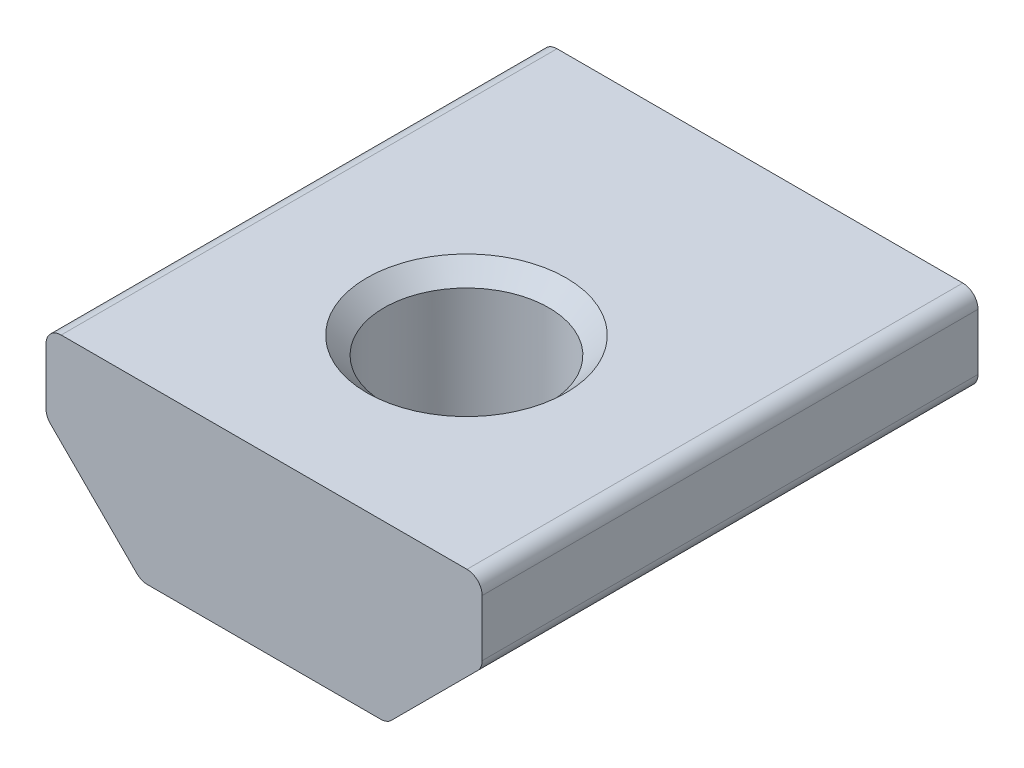
SolidWorks part; units mm, degrees
ref_plane "Front Plane" through (0, 0, 0) normal (0, 0, 1) x (1, 0, 0)
ref_plane "Top Plane" through (0, 0, 0) normal (0, 1, 0) x (1, 0, 0)
ref_plane "Right Plane" through (0, 0, 0) normal (1, 0, 0) x (0, 0, -1)
ref_plane "Plane1" through (0, 0, 5.08) normal (0, 0, 1) x (1, 0, 0)
sketch "Sketch1" plane through (0, 0, 5.08) normal (0, 0, 1) x (1, 0, 0)
  line L0 (5.4737, 4.3434) -> (-5.4737, 4.3434)
  line L1 (-5.4737, 4.3434) -> (-5.4737, 2.3889)
  line L2 (-5.4737, 2.3889) -> (-3.0848, 0)
  line L3 (-3.0848, 0) -> (3.0848, 0)
  line L4 (3.0848, 0) -> (5.4737, 2.3889)
  line L5 (5.4737, 2.3889) -> (5.4737, 4.3434)
extrude "Boss-Extrude1" add sketch "Sketch1" against normal blind 12.446
hole_wizard "#6 Clearance Hole1" positions "Sketch3" profile "Sketch2" hole size "#6" standard "ANSI Inch"
sketch "Sketch3" plane through (0, 4.3434, 0) normal (0, 1, 0) x (1, 0, 0)
  point P0 (0, 0)
sketch "Sketch2" plane through (0, 4.3434, 0) normal (1, 0, 0) x (0, 0, 1)
  line L0 (0, 0) -> (0, 4.3434)
  line L1 (0, 4.3434) -> (2.067, 4.3434)
  line L2 (2.067, 4.3434) -> (2.067, 0)
  line L5 (2.067, 0) -> (0, 0)
  line L11 (0, -6.35) -> (0, 107.95) construction
  dimension "Thru Hole Dia." = 4.134
  dimension "Thru Hole Depth" = 4.3434
chamfer "Chamfer1" distance 0.433 angle 45 2 edges at (0, 0, 2.067) (0, 4.3434, 2.067)
fillet "Fillet1" radius 0.381 6 edges at (-3.0848, 0, -1.143) (-5.4737, 4.3434, -1.143) (-5.4737, 2.3889, -1.143) (5.4737, 4.3434, -1.143) (3.0848, 0, -1.143) (5.4737, 2.3889, -1.143)
